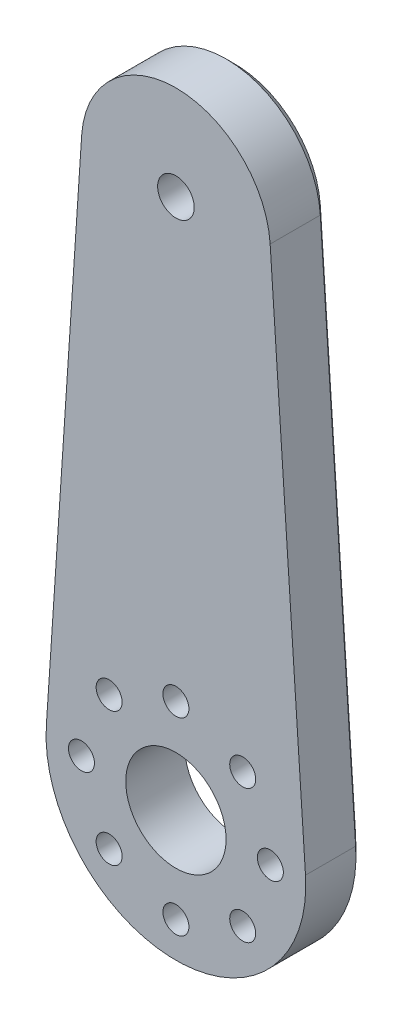
SolidWorks part; units mm, degrees
ref_plane "Front Plane" through (0, 0, 0) normal (0, 0, 1) x (1, 0, 0)
ref_plane "Top Plane" through (0, 0, 0) normal (0, 1, 0) x (1, 0, 0)
ref_plane "Right Plane" through (0, 0, 0) normal (1, 0, 0) x (0, 0, -1)
sketch "Sketch1" plane through (0, 0, 0) normal (0, 0, 1) x (1, 0, 0)
  line L0 (-23.1158, 26.3761) -> (-26.1092, -18.4239)
  line L3 (-7.1514, 26.3761) -> (-4.1581, -18.4239)
  line L4 (-15.1336, 0.8298) -> (-15.1336, 20.8298) construction
  line L5 (-14.7824, -19.1572) -> (49985.2176, -19.1572) construction
  circle A2 centre (-15.1336, 25.8428) radius 1.55
  circle A3 centre (-15.1336, -19.1572) radius 4.25
  arc A5 (-7.1514, 26.3761) -> (-23.1158, 26.3761) centre (-15.1336, 25.8428) ccw
  arc A6 (-26.1092, -18.4239) -> (-4.1581, -18.4239) centre (-15.1336, -19.1572) ccw
  circle A7 centre (-15.0314, -20.0888) radius 11 construction
  circle A8 centre (-7.1336, -19.1572) radius 1.1
  circle A9 centre (-9.4768, -24.8141) radius 1.1
  circle A10 centre (-15.1336, -27.1572) radius 1.1
  circle A11 centre (-20.7905, -24.8141) radius 1.1
  circle A12 centre (-23.1336, -19.1572) radius 1.1
  circle A13 centre (-20.7905, -13.5004) radius 1.1
  circle A14 centre (-15.1336, -11.1572) radius 1.1
  circle A15 centre (-9.4768, -13.5004) radius 1.1
  point P30 (-15.1336, -19.1572)
  dimension "D1" = 3.1
  dimension "D3" = 45
  dimension "D4" = 11
  dimension "D2" = 8
  dimension "D5" = 8.5
  dimension "D6" = 2.2
  dimension "D7" = 8
  dimension "D8" = 8
extrude "Boss-Extrude1" add sketch "Sketch1" along normal blind 5
sketch "Sketch2" plane through (0, 0, 5) normal (0, 0, 1) x (1, 0, 0)
  circle A0 centre (-15.1336, -19.1572) radius 11.5
  dimension "D1" = 23
extrude "Cut-Extrude1" [suppressed] cut sketch "Sketch2" against normal blind 1.75
sketch "Sketch3" plane through (0, 0, 0) normal (0, 0, 1) x (1, 0, 0)
  line L1 (-13.5459, 23.0928) -> (-11.9582, 25.8428)
  line L2 (-11.9582, 25.8428) -> (-13.5459, 28.5928)
  line L3 (-13.5459, 28.5928) -> (-16.7214, 28.5928)
  line L4 (-16.7214, 28.5928) -> (-18.3091, 25.8428)
  line L5 (-18.3091, 25.8428) -> (-16.7214, 23.0928)
  line L6 (-16.7214, 23.0928) -> (-13.5459, 23.0928)
  circle A0 centre (-15.1336, 25.8428) radius 2.75 construction
  dimension "D1" = 5.5
extrude "Cut-Extrude2" cut sketch "Sketch3" along normal blind 2
sketch "Sketch5" plane through (0, 0, 5) normal (0, 0, 1) x (1, 0, 0)
  circle A2 centre (-14.8897, 3.8764) radius 1.55
  circle A3 centre (-14.8897, 3.8764) radius 8
extrude "Boss-Extrude2" [suppressed] add sketch "Sketch5" along normal blind 3
fillet "Fillet1" [suppressed] radius 1
sketch "Sketch4" plane through (0, 0, 0) normal (0, 0, -1) x (-1, 0, 0)
  circle A0 centre (23.1336, -19.1572) radius 1.75
  circle A1 centre (20.7905, -24.8141) radius 1.75
  circle A2 centre (15.1336, -27.1572) radius 1.75
  circle A3 centre (9.4768, -24.8141) radius 1.75
  circle A4 centre (7.1336, -19.1572) radius 1.75
  circle A5 centre (9.4768, -13.5004) radius 1.75
  circle A6 centre (15.1336, -11.1572) radius 1.75
  circle A7 centre (20.7905, -13.5004) radius 1.75
  circle A10 centre (15.1336, -19.1572) radius 4.25 construction
  point P20 (15.1336, -19.1572)
  dimension "D1" = 3.5
extrude "Cut-Extrude3" cut sketch "Sketch4" against normal blind 2.25
chamfer "Chaflán1" distance 0.75 angle 45 4 edges at (-24.6125, 3.9761, 0) (-15.1336, -30.1572, 0) (-15.1336, 33.8428, 0) (-5.6548, 3.9761, 0)
